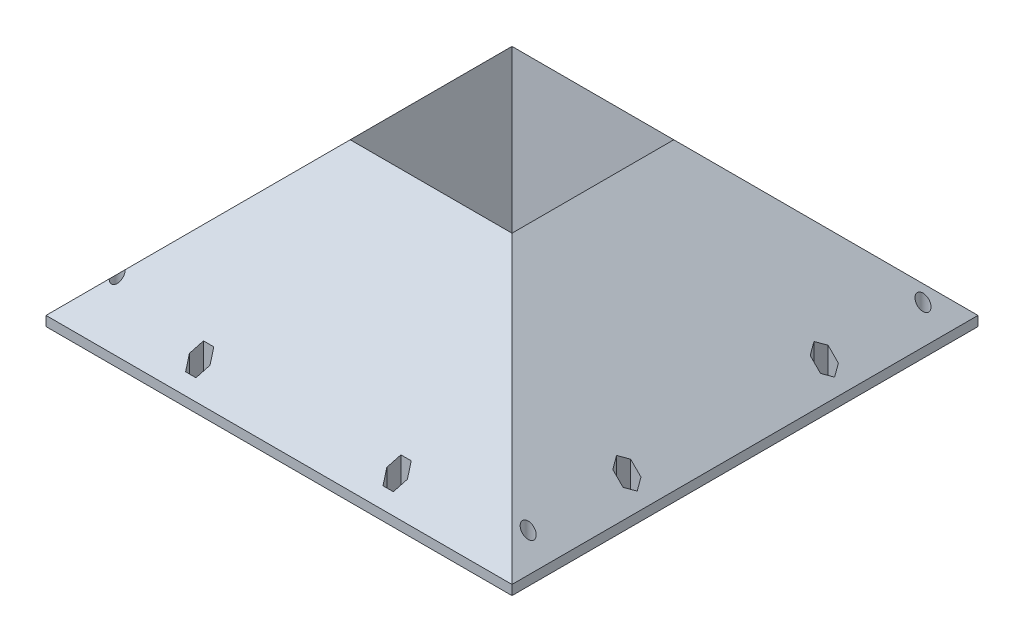
SolidWorks part; units mm, degrees
ref_plane "Alzado" through (0, 0, 0) normal (0, 0, 1) x (1, 0, 0)
ref_plane "Planta" through (0, 0, 0) normal (0, 1, 0) x (1, 0, 0)
ref_plane "Vista lateral" through (0, 0, 0) normal (1, 0, 0) x (0, 0, -1)
sketch "Croquis1" plane through (0, 0, 0) normal (0, 1, 0) x (1, 0, 0)
  line L0 (0, 0) -> (-62.5, 0) construction
  line L1 (-62.5, 0) -> (-62.5, 55) construction
  line L2 (-62.5, 55) -> (-55, 62.5) construction
  line L3 (-55, 62.5) -> (0, 62.5) construction
  line L4 (0, 62.5) -> (0, 0) construction
  line L5 (62.5, 55) -> (62.5, 0) construction
  line L6 (55, 62.5) -> (62.5, 55) construction
  line L7 (0, 62.5) -> (55, 62.5) construction
  line L8 (55, -62.5) -> (0, -62.5) construction
  line L9 (62.5, -55) -> (55, -62.5) construction
  line L10 (62.5, 0) -> (62.5, -55) construction
  line L11 (-62.5, -55) -> (-62.5, 0) construction
  line L12 (-55, -62.5) -> (-62.5, -55) construction
  line L13 (0, -62.5) -> (-55, -62.5) construction
  line L14 (0, -70) -> (0, -62.5) construction
  line L15 (0, 0) -> (-61, 0) construction
  line L16 (0, 0) -> (0, 61) construction
  line L17 (0, 61) -> (-61, 61) construction
  line L18 (-61, 0) -> (-61, 61) construction
  line L19 (0, 0) -> (-61, 0) construction
  line L20 (0, 0) -> (0, -61) construction
  line L21 (0, -61) -> (-61, -61) construction
  line L22 (-61, 0) -> (-61, -61) construction
  line L23 (0, 0) -> (66, 0) construction
  line L24 (0, 0) -> (0, -61) construction
  line L25 (0, -61) -> (66, -61) construction
  line L26 (66, 0) -> (66, -61) construction
  line L27 (0, 0) -> (66, 0) construction
  line L28 (0, 0) -> (0, 61) construction
  line L29 (0, 61) -> (66, 61) construction
  line L30 (66, 0) -> (66, 61) construction
  line L35 (25, -25) -> (-25, 25) construction
  line L36 (25, 25) -> (-25, -25) construction
  line L37 (70, -70) -> (-70, -70)
  line L38 (70, -70) -> (70, 70)
  line L39 (70, 70) -> (-70, 70)
  line L40 (-70, -70) -> (-70, 70)
  line L41 (70, -70) -> (-70, 70) construction
  line L42 (70, 70) -> (-70, -70) construction
  line L43 (-30.5, -66) -> (30.5, -66) construction
  circle A0 centre (-61, 61) radius 1.5
  circle A1 centre (66, 61) radius 1.5
  circle A2 centre (66, -61) radius 1.5
  circle A3 centre (-61, -61) radius 1.5
  circle A4 centre (66, 30.5) radius 1.5
  circle A5 centre (66, -30.5) radius 1.5
  circle A6 centre (-30.5, -66) radius 1.5
  circle A7 centre (30.5, -66) radius 1.5
  circle A8 centre (-30.5, 66) radius 1.5
  circle A9 centre (30.5, 66) radius 1.5
  circle A10 centre (-66, 30.5) radius 1.5
  circle A11 centre (-66, -30.5) radius 1.5
  point P48 (0, -66)
  dimension "D6" = 3
  dimension "D9" = 4
  dimension "D10" = 3
  dimension "D1" = 55
  dimension "D2" = 62.5
  dimension "D4" = 61
  dimension "D5" = 66
  dimension "D7" = 50
  dimension "D8" = 140
  dimension "D11" = 61
  dimension "D3" = 4
extrude "Saliente-Extruir1" add sketch "Croquis1" along normal blind 50
sketch "Croquis2" plane through (0, 50, 0) normal (0, 1, 0) x (1, 0, 0)
  line L1 (-28.9065, 63.24) -> (-27.313, 66)
  line L2 (-27.313, 66) -> (-28.9065, 68.76)
  line L3 (-28.9065, 68.76) -> (-32.0935, 68.76)
  line L4 (-32.0935, 68.76) -> (-33.687, 66)
  line L5 (-33.687, 66) -> (-32.0935, 63.24)
  line L6 (-32.0935, 63.24) -> (-28.9065, 63.24)
  line L7 (32.0935, 63.24) -> (33.687, 66)
  line L8 (33.687, 66) -> (32.0935, 68.76)
  line L9 (32.0935, 68.76) -> (28.9065, 68.76)
  line L10 (28.9065, 68.76) -> (27.313, 66)
  line L11 (27.313, 66) -> (28.9065, 63.24)
  line L12 (28.9065, 63.24) -> (32.0935, 63.24)
  line L13 (67.5935, 27.74) -> (69.187, 30.5)
  line L14 (69.187, 30.5) -> (67.5935, 33.26)
  line L15 (67.5935, 33.26) -> (64.4065, 33.26)
  line L16 (64.4065, 33.26) -> (62.813, 30.5)
  line L17 (62.813, 30.5) -> (64.4065, 27.74)
  line L18 (64.4065, 27.74) -> (67.5935, 27.74)
  line L19 (67.5935, -33.26) -> (69.187, -30.5)
  line L20 (69.187, -30.5) -> (67.5935, -27.74)
  line L21 (67.5935, -27.74) -> (64.4065, -27.74)
  line L22 (64.4065, -27.74) -> (62.813, -30.5)
  line L23 (62.813, -30.5) -> (64.4065, -33.26)
  line L24 (64.4065, -33.26) -> (67.5935, -33.26)
  line L25 (32.0935, -68.76) -> (33.687, -66)
  line L26 (33.687, -66) -> (32.0935, -63.24)
  line L27 (32.0935, -63.24) -> (28.9065, -63.24)
  line L28 (28.9065, -63.24) -> (27.313, -66)
  line L29 (27.313, -66) -> (28.9065, -68.76)
  line L30 (28.9065, -68.76) -> (32.0935, -68.76)
  line L31 (-28.9065, -68.76) -> (-27.313, -66)
  line L32 (-27.313, -66) -> (-28.9065, -63.24)
  line L33 (-28.9065, -63.24) -> (-32.0935, -63.24)
  line L34 (-32.0935, -63.24) -> (-33.687, -66)
  line L35 (-33.687, -66) -> (-32.0935, -68.76)
  line L36 (-32.0935, -68.76) -> (-28.9065, -68.76)
  line L37 (-64.4065, -33.26) -> (-62.813, -30.5)
  line L38 (-62.813, -30.5) -> (-64.4065, -27.74)
  line L39 (-64.4065, -27.74) -> (-67.5935, -27.74)
  line L40 (-67.5935, -27.74) -> (-69.187, -30.5)
  line L41 (-69.187, -30.5) -> (-67.5935, -33.26)
  line L42 (-67.5935, -33.26) -> (-64.4065, -33.26)
  line L43 (-64.4065, 27.74) -> (-62.813, 30.5)
  line L44 (-62.813, 30.5) -> (-64.4065, 33.26)
  line L45 (-64.4065, 33.26) -> (-67.5935, 33.26)
  line L46 (-67.5935, 33.26) -> (-69.187, 30.5)
  line L47 (-69.187, 30.5) -> (-67.5935, 27.74)
  line L48 (-67.5935, 27.74) -> (-64.4065, 27.74)
  line L49 (-25, 25) -> (25, 25)
  line L50 (-25, 25) -> (-25, -25)
  line L51 (-25, -25) -> (25, -25)
  line L52 (25, 25) -> (25, -25)
  line L53 (-25, 25) -> (25, -25) construction
  line L54 (-25, -25) -> (25, 25) construction
  circle A0 centre (-30.5, 66) radius 2.76 construction
  circle A1 centre (30.5, 66) radius 2.76 construction
  circle A2 centre (66, 30.5) radius 2.76 construction
  circle A3 centre (66, -30.5) radius 2.76 construction
  circle A4 centre (30.5, -66) radius 2.76 construction
  circle A5 centre (-30.5, -66) radius 2.76 construction
  circle A6 centre (-66, -30.5) radius 2.76 construction
  circle A7 centre (-66, 30.5) radius 2.76 construction
  circle A8 centre (66, 61) radius 1.75
  circle A9 centre (-61, 61) radius 1.75
  circle A10 centre (-61, -61) radius 1.75
  circle A11 centre (66, -61) radius 1.75
  point P64 (0, 0)
  dimension "D3" = 3.5
  dimension "D1" = 5.52
  dimension "D2" = 50
extrude "Cortar-Extruir1" cut sketch "Croquis2" against normal blind 143
sketch "Croquis3" plane through (0, 50, 0) normal (0, 1, 0) x (1, 0, 0)
  line L0 (-25, -25) -> (25, -25) construction
  line L1 (-25, 25) -> (-25, -25) construction
  line L12 (-33.687, -66) -> (-32.0935, -68.76) construction
  line L13 (-32.0935, -68.76) -> (-28.9065, -68.76) construction
  line L14 (-28.9065, -68.76) -> (-27.313, -66) construction
  line L15 (-27.313, -66) -> (-28.9065, -63.24) construction
  line L16 (-28.9065, -63.24) -> (-32.0935, -63.24) construction
  line L17 (-32.0935, -63.24) -> (-33.687, -66) construction
  line L18 (-67.5935, -33.26) -> (-64.4065, -33.26) construction
  line L19 (-69.187, -30.5) -> (-67.5935, -33.26) construction
  line L20 (-67.5935, -27.74) -> (-69.187, -30.5) construction
  line L21 (-64.4065, -27.74) -> (-67.5935, -27.74) construction
  line L22 (-62.813, -30.5) -> (-64.4065, -27.74) construction
  line L23 (-64.4065, -33.26) -> (-62.813, -30.5) construction
  line L24 (-25, 25) -> (-25, -25)
  line L25 (-25, -25) -> (25, -25)
  line L26 (-33.687, -66) -> (-32.0935, -68.76)
  line L27 (-32.0935, -68.76) -> (-28.9065, -68.76)
  line L28 (-28.9065, -68.76) -> (-27.313, -66)
  line L29 (-27.313, -66) -> (-28.9065, -63.24)
  line L30 (-28.9065, -63.24) -> (-32.0935, -63.24)
  line L31 (-32.0935, -63.24) -> (-33.687, -66)
  line L32 (-67.5935, -33.26) -> (-64.4065, -33.26)
  line L33 (-69.187, -30.5) -> (-67.5935, -33.26)
  line L34 (-67.5935, -27.74) -> (-69.187, -30.5)
  line L35 (-64.4065, -27.74) -> (-67.5935, -27.74)
  line L36 (-62.813, -30.5) -> (-64.4065, -27.74)
  line L37 (-64.4065, -33.26) -> (-62.813, -30.5)
  line L38 (28.9065, 63.24) -> (32.0935, 63.24) construction
  line L39 (32.0935, 63.24) -> (33.687, 66) construction
  line L40 (33.687, 66) -> (32.0935, 68.76) construction
  line L41 (32.0935, 68.76) -> (28.9065, 68.76) construction
  line L42 (28.9065, 68.76) -> (27.313, 66) construction
  line L43 (27.313, 66) -> (28.9065, 63.24) construction
  line L44 (-33.687, 66) -> (-32.0935, 63.24) construction
  line L45 (-32.0935, 68.76) -> (-33.687, 66) construction
  line L46 (-28.9065, 68.76) -> (-32.0935, 68.76) construction
  line L47 (-27.313, 66) -> (-28.9065, 68.76) construction
  line L48 (-28.9065, 63.24) -> (-27.313, 66) construction
  line L49 (-32.0935, 63.24) -> (-28.9065, 63.24) construction
  line L50 (62.813, 30.5) -> (64.4065, 27.74) construction
  line L51 (64.4065, 27.74) -> (67.5935, 27.74) construction
  line L52 (67.5935, 27.74) -> (69.187, 30.5) construction
  line L53 (69.187, 30.5) -> (67.5935, 33.26) construction
  line L54 (64.4065, 33.26) -> (62.813, 30.5) construction
  line L55 (67.5935, 33.26) -> (64.4065, 33.26) construction
  line L56 (67.5935, -33.26) -> (69.187, -30.5) construction
  line L57 (69.187, -30.5) -> (67.5935, -27.74) construction
  line L58 (67.5935, -27.74) -> (64.4065, -27.74) construction
  line L59 (64.4065, -27.74) -> (62.813, -30.5) construction
  line L60 (62.813, -30.5) -> (64.4065, -33.26) construction
  line L61 (64.4065, -33.26) -> (67.5935, -33.26) construction
  line L62 (33.687, -66) -> (32.0935, -63.24) construction
  line L63 (32.0935, -68.76) -> (33.687, -66) construction
  line L64 (28.9065, -68.76) -> (32.0935, -68.76) construction
  line L65 (27.313, -66) -> (28.9065, -68.76) construction
  line L66 (25, -25) -> (25, 25) construction
  line L67 (28.9065, -63.24) -> (27.313, -66) construction
  line L68 (32.0935, -63.24) -> (28.9065, -63.24) construction
  line L69 (28.9065, 63.24) -> (32.0935, 63.24)
  line L70 (32.0935, 63.24) -> (33.687, 66)
  line L71 (33.687, 66) -> (32.0935, 68.76)
  line L72 (32.0935, 68.76) -> (28.9065, 68.76)
  line L73 (28.9065, 68.76) -> (27.313, 66)
  line L74 (27.313, 66) -> (28.9065, 63.24)
  line L75 (-33.687, 66) -> (-32.0935, 63.24)
  line L76 (-32.0935, 68.76) -> (-33.687, 66)
  line L77 (-28.9065, 68.76) -> (-32.0935, 68.76)
  line L78 (-27.313, 66) -> (-28.9065, 68.76)
  line L79 (-28.9065, 63.24) -> (-27.313, 66)
  line L80 (-32.0935, 63.24) -> (-28.9065, 63.24)
  line L81 (62.813, 30.5) -> (64.4065, 27.74)
  line L82 (64.4065, 27.74) -> (67.5935, 27.74)
  line L83 (67.5935, 27.74) -> (69.187, 30.5)
  line L84 (69.187, 30.5) -> (67.5935, 33.26)
  line L85 (64.4065, 33.26) -> (62.813, 30.5)
  line L86 (67.5935, 33.26) -> (64.4065, 33.26)
  line L87 (67.5935, -33.26) -> (69.187, -30.5)
  line L88 (69.187, -30.5) -> (67.5935, -27.74)
  line L89 (67.5935, -27.74) -> (64.4065, -27.74)
  line L90 (64.4065, -27.74) -> (62.813, -30.5)
  line L91 (62.813, -30.5) -> (64.4065, -33.26)
  line L92 (64.4065, -33.26) -> (67.5935, -33.26)
  line L93 (33.687, -66) -> (32.0935, -63.24)
  line L94 (32.0935, -68.76) -> (33.687, -66)
  line L95 (28.9065, -68.76) -> (32.0935, -68.76)
  line L96 (27.313, -66) -> (28.9065, -68.76)
  line L97 (25, -25) -> (25, 25)
  line L98 (28.9065, -63.24) -> (27.313, -66)
  line L99 (32.0935, -63.24) -> (28.9065, -63.24)
  line L100 (-64.4065, 27.74) -> (-62.813, 30.5) construction
  line L101 (-67.5935, 27.74) -> (-64.4065, 27.74) construction
  line L102 (-69.187, 30.5) -> (-67.5935, 27.74) construction
  line L103 (-67.5935, 33.26) -> (-69.187, 30.5) construction
  line L104 (-64.4065, 33.26) -> (-67.5935, 33.26) construction
  line L105 (-62.813, 30.5) -> (-64.4065, 33.26) construction
  line L106 (-64.4065, 27.74) -> (-62.813, 30.5)
  line L107 (-67.5935, 27.74) -> (-64.4065, 27.74)
  line L108 (-69.187, 30.5) -> (-67.5935, 27.74)
  line L109 (-67.5935, 33.26) -> (-69.187, 30.5)
  line L110 (-64.4065, 33.26) -> (-67.5935, 33.26)
  line L111 (-62.813, 30.5) -> (-64.4065, 33.26)
  line L112 (25, 25) -> (-25, 25) construction
  line L113 (25, 25) -> (-25, 25)
  line L116 (-72, -72) -> (72, -72)
  line L117 (-72, 72) -> (-72, -72)
  line L118 (72, 72) -> (-72, 72)
  line L119 (72, -72) -> (72, 72)
  line L120 (-72, -72) -> (72, -72)
  line L121 (-72, 72) -> (-72, -72)
  line L122 (72, 72) -> (-72, 72)
  line L123 (72, -72) -> (72, 72)
  circle A0 centre (-61, -61) radius 1.75 construction
  circle A1 centre (-61, -61) radius 1.75
  circle A2 centre (-61, 61) radius 1.75 construction
  circle A3 centre (66, 61) radius 1.75 construction
  circle A4 centre (66, -61) radius 1.75 construction
  circle A5 centre (-61, 61) radius 1.75
  circle A6 centre (66, 61) radius 1.75
  circle A7 centre (66, -61) radius 1.75
  dimension "D1" = 2
extrude "Saliente-Extruir3" add sketch "Croquis3" against normal up to surface (50 mm away)
sketch "Croquis4" plane through (-72, 0, 0) normal (-1, 0, 0) x (0, 0, 1)
  line L0 (-25, 50) -> (-72, 3)
  line L1 (-72, 0) -> (-72, 50) construction
  line L2 (-72, 50) -> (72, 50) construction
  line L3 (72, 0) -> (72, 50) construction
  line L4 (72, 3) -> (72, 50)
  line L5 (-72, 3) -> (-72, 50)
  line L6 (-72, 50) -> (-25, 50)
  line L7 (25, 50) -> (72, 3)
  line L8 (25, 50) -> (72, 50)
  dimension "D1" = 45
  dimension "D2" = 45
extrude "Cortar-Extruir2" cut sketch "Croquis4" against normal up to surface (144 mm away) up to face at (72, 25, 0)
sketch "Croquis5" plane through (0, 0, 0) normal (0, 0, 1) x (1, 0, 0)
  line L0 (-25, 50) -> (-72, 3)
  line L1 (-25, 50) -> (-72, 50) construction
  line L2 (-72, 50) -> (-72, 3) construction
  line L3 (-25, 50) -> (-72, 50)
  line L4 (-72, 50) -> (-72, 3)
  line L5 (25, 50) -> (72, 3)
  line L6 (72, 50) -> (25, 50) construction
  line L7 (72, 50) -> (72, 3) construction
  line L8 (72, 50) -> (25, 50)
  line L9 (72, 50) -> (72, 3)
extrude "Cortar-Extruir3" cut sketch "Croquis5" against normal blind 78 and the other way blind 92
